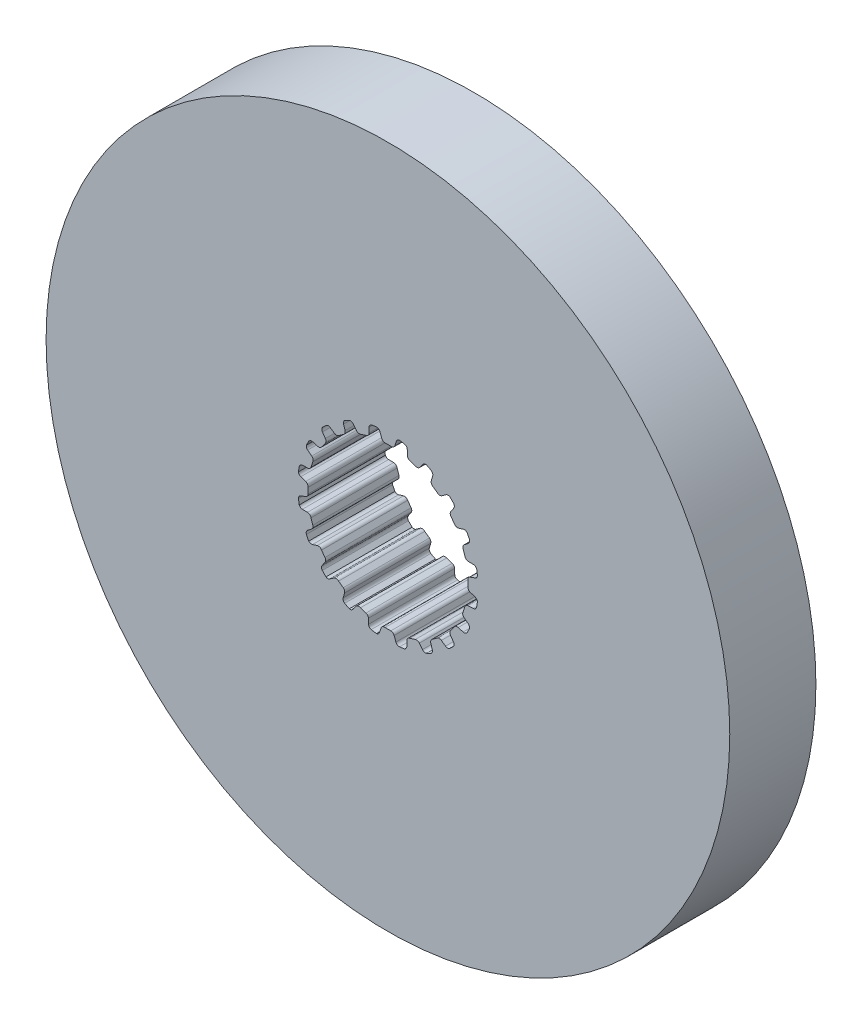
SolidWorks part; units mm, degrees
ref_plane "Front Plane" through (0, 0, 0) normal (0, 0, 1) x (1, 0, 0)
ref_plane "Top Plane" through (0, 0, 0) normal (0, 1, 0) x (1, 0, 0)
ref_plane "Right Plane" through (0, 0, 0) normal (1, 0, 0) x (0, 0, -1)
sketch "Sketch1" plane through (0, 0, 0) normal (0, 0, 1) x (1, 0, 0)
  line L0 (-0.1069, 2.9699) -> (0.1069, 2.9699)
  line L1 (0.3159, 3.2375) -> (0.2537, 3.0575)
  line L2 (-0.2964, 3.2367) -> (-0.2318, 3.0575)
  line L3 (-0.2964, 3.2367) -> (0.3159, 3.2375) construction
  line L4 (0, 3.3252) -> (0, 0) construction
  line L5 (-0.2318, 3.0575) -> (0.2537, 3.0575) construction
  line L6 (-0.4281, 3.3241) -> (0.4281, 3.3263) construction
  line L7 (0.7183, 3.1698) -> (0.7244, 2.9795)
  line L8 (0.816, 2.8576) -> (1.0195, 2.7915)
  line L9 (1.3009, 2.9815) -> (1.1862, 2.8295)
  line L10 (1.6627, 2.7927) -> (1.6097, 2.6099)
  line L11 (1.6591, 2.4655) -> (1.8322, 2.3398)
  line L12 (2.1585, 2.4335) -> (2.0025, 2.3245)
  line L13 (2.4443, 2.1423) -> (2.3374, 1.9847)
  line L14 (2.3398, 1.8322) -> (2.4655, 1.6591)
  line L15 (2.8049, 1.6474) -> (2.6228, 1.5919)
  line L16 (2.9866, 1.2821) -> (2.8363, 1.1653)
  line L17 (2.7915, 1.0195) -> (2.8576, 0.816)
  line L18 (3.1767, 0.7) -> (2.9863, 0.7035)
  line L19 (3.2367, 0.2964) -> (3.0575, 0.2318)
  line L20 (2.9699, 0.1069) -> (2.9699, -0.1069)
  line L21 (3.2375, -0.3159) -> (3.0575, -0.2537)
  line L22 (3.1698, -0.7183) -> (2.9795, -0.7244)
  line L23 (2.8576, -0.816) -> (2.7915, -1.0195)
  line L24 (2.9815, -1.3009) -> (2.8295, -1.1862)
  line L25 (2.7927, -1.6627) -> (2.6099, -1.6097)
  line L26 (2.4655, -1.6591) -> (2.3398, -1.8322)
  line L27 (2.4335, -2.1585) -> (2.3245, -2.0025)
  line L28 (2.1423, -2.4443) -> (1.9847, -2.3374)
  line L29 (1.8322, -2.3398) -> (1.6591, -2.4655)
  line L30 (1.6474, -2.8049) -> (1.5919, -2.6228)
  line L31 (1.2821, -2.9866) -> (1.1653, -2.8363)
  line L32 (1.0195, -2.7915) -> (0.816, -2.8576)
  line L33 (0.7, -3.1767) -> (0.7035, -2.9863)
  line L34 (0.2964, -3.2367) -> (0.2318, -3.0575)
  line L35 (0.1069, -2.9699) -> (-0.1069, -2.9699)
  line L36 (-0.3159, -3.2375) -> (-0.2537, -3.0575)
  line L37 (-0.7183, -3.1698) -> (-0.7244, -2.9795)
  line L38 (-0.816, -2.8576) -> (-1.0195, -2.7915)
  line L39 (-1.3009, -2.9815) -> (-1.1862, -2.8295)
  line L40 (-1.6627, -2.7927) -> (-1.6097, -2.6099)
  line L41 (-1.6591, -2.4655) -> (-1.8322, -2.3398)
  line L42 (-2.1585, -2.4335) -> (-2.0025, -2.3245)
  line L43 (-2.4443, -2.1423) -> (-2.3374, -1.9847)
  line L44 (-2.3398, -1.8322) -> (-2.4655, -1.6591)
  line L45 (-2.8049, -1.6474) -> (-2.6228, -1.5919)
  line L46 (-2.9866, -1.2821) -> (-2.8363, -1.1653)
  line L47 (-2.7915, -1.0195) -> (-2.8576, -0.816)
  line L48 (-3.1767, -0.7) -> (-2.9863, -0.7035)
  line L49 (-3.2367, -0.2964) -> (-3.0575, -0.2318)
  line L50 (-2.9699, -0.1069) -> (-2.9699, 0.1069)
  line L51 (-3.2375, 0.3159) -> (-3.0575, 0.2537)
  line L52 (-3.1698, 0.7183) -> (-2.9795, 0.7244)
  line L53 (-2.8576, 0.816) -> (-2.7915, 1.0195)
  line L54 (-2.9815, 1.3009) -> (-2.8295, 1.1862)
  line L55 (-2.7927, 1.6627) -> (-2.6099, 1.6097)
  line L56 (-2.4655, 1.6591) -> (-2.3398, 1.8322)
  line L57 (-2.4335, 2.1585) -> (-2.3245, 2.0025)
  line L58 (-2.1423, 2.4443) -> (-1.9847, 2.3374)
  line L59 (-1.8322, 2.3398) -> (-1.6591, 2.4655)
  line L60 (-1.6474, 2.8049) -> (-1.5919, 2.6228)
  line L61 (-1.2821, 2.9866) -> (-1.1653, 2.8363)
  line L62 (-1.0195, 2.7915) -> (-0.816, 2.8576)
  line L63 (-0.7, 3.1767) -> (-0.7035, 2.9863)
  line L64 (0.4281, 3.3263) -> (0.62, 3.2938)
  line L65 (1.4351, 3.0312) -> (1.6075, 2.9409)
  line L66 (2.3015, 2.4394) -> (2.4376, 2.3003)
  line L67 (2.9427, 1.6088) -> (3.0291, 1.4344)
  line L68 (3.2958, 0.6207) -> (3.3241, 0.4281)
  line L69 (3.3263, -0.4281) -> (3.2938, -0.62)
  line L70 (3.0312, -1.4351) -> (2.9409, -1.6075)
  line L71 (2.4394, -2.3015) -> (2.3003, -2.4376)
  line L72 (1.6088, -2.9427) -> (1.4344, -3.0291)
  line L73 (0.6207, -3.2958) -> (0.4281, -3.3241)
  line L74 (-0.4281, -3.3263) -> (-0.62, -3.2938)
  line L75 (-1.4351, -3.0312) -> (-1.6075, -2.9409)
  line L76 (-2.3015, -2.4394) -> (-2.4376, -2.3003)
  line L77 (-2.9427, -1.6088) -> (-3.0291, -1.4344)
  line L78 (-3.2958, -0.6207) -> (-3.3241, -0.4281)
  line L79 (-3.3263, 0.4281) -> (-3.2938, 0.62)
  line L80 (-3.0312, 1.4351) -> (-2.9409, 1.6075)
  line L81 (-2.4394, 2.3015) -> (-2.3003, 2.4376)
  line L82 (-1.6088, 2.9427) -> (-1.4344, 3.0291)
  line L83 (-0.6207, 3.2958) -> (-0.4281, 3.3241)
  arc A0 (0.2537, 3.0575) -> (0.1069, 2.9699) centre (0.1283, 3.1009) cw
  arc A1 (-0.2318, 3.0575) -> (-0.1069, 2.9699) centre (-0.1069, 3.1026) ccw
  arc A2 (0.62, 3.2938) -> (0.7183, 3.1698) centre (0.5856, 3.1656) cw
  arc A3 (0.7244, 2.9795) -> (0.816, 2.8576) centre (0.857, 2.9838) ccw
  arc A4 (-0.4281, 3.3241) -> (-0.2964, 3.2367) centre (-0.4213, 3.1916) cw
  arc A5 (0.4281, 3.3263) -> (0.3159, 3.2375) centre (0.4413, 3.1942) ccw
  arc A6 (1.1862, 2.8295) -> (1.0195, 2.7915) centre (1.0802, 2.9095) cw
  arc A7 (1.4351, 3.0312) -> (1.3009, 2.9815) centre (1.4068, 2.9015) ccw
  arc A8 (1.6075, 2.9409) -> (1.6627, 2.7927) centre (1.5352, 2.8297) cw
  arc A9 (1.6097, 2.6099) -> (1.6591, 2.4655) centre (1.7371, 2.5729) ccw
  arc A10 (2.0025, 2.3245) -> (1.8322, 2.3398) centre (1.9264, 2.4332) cw
  arc A11 (2.3015, 2.4394) -> (2.1585, 2.4335) centre (2.2346, 2.3248) ccw
  arc A12 (2.4376, 2.3003) -> (2.4443, 2.1423) centre (2.3345, 2.2168) cw
  arc A13 (2.3374, 1.9847) -> (2.3398, 1.8322) centre (2.4472, 1.9102) ccw
  arc A14 (2.6228, 1.5919) -> (2.4655, 1.6591) centre (2.5841, 1.7189) cw
  arc A15 (2.9427, 1.6088) -> (2.8049, 1.6474) centre (2.8436, 1.5205) ccw
  arc A16 (3.0291, 1.4344) -> (2.9866, 1.2821) centre (2.9052, 1.3869) cw
  arc A17 (2.8363, 1.1653) -> (2.7915, 1.0195) centre (2.9177, 1.0605) ccw
  arc A18 (2.9863, 0.7035) -> (2.8576, 0.816) centre (2.9887, 0.8362) cw
  arc A19 (3.2958, 0.6207) -> (3.1767, 0.7) centre (3.1743, 0.5673) ccw
  arc A20 (3.3241, 0.4281) -> (3.2367, 0.2964) centre (3.1916, 0.4213) cw
  arc A21 (3.0575, 0.2318) -> (2.9699, 0.1069) centre (3.1026, 0.1069) ccw
  arc A22 (3.0575, -0.2537) -> (2.9699, -0.1069) centre (3.1009, -0.1283) cw
  arc A23 (3.3263, -0.4281) -> (3.2375, -0.3159) centre (3.1942, -0.4413) ccw
  arc A24 (3.2938, -0.62) -> (3.1698, -0.7183) centre (3.1656, -0.5856) cw
  arc A25 (2.9795, -0.7244) -> (2.8576, -0.816) centre (2.9838, -0.857) ccw
  arc A26 (2.8295, -1.1862) -> (2.7915, -1.0195) centre (2.9095, -1.0802) cw
  arc A27 (3.0312, -1.4351) -> (2.9815, -1.3009) centre (2.9015, -1.4068) ccw
  arc A28 (2.9409, -1.6075) -> (2.7927, -1.6627) centre (2.8297, -1.5352) cw
  arc A29 (2.6099, -1.6097) -> (2.4655, -1.6591) centre (2.5729, -1.7371) ccw
  arc A30 (2.3245, -2.0025) -> (2.3398, -1.8322) centre (2.4332, -1.9264) cw
  arc A31 (2.4394, -2.3015) -> (2.4335, -2.1585) centre (2.3248, -2.2346) ccw
  arc A32 (2.3003, -2.4376) -> (2.1423, -2.4443) centre (2.2168, -2.3345) cw
  arc A33 (1.9847, -2.3374) -> (1.8322, -2.3398) centre (1.9102, -2.4472) ccw
  arc A34 (1.5919, -2.6228) -> (1.6591, -2.4655) centre (1.7189, -2.5841) cw
  arc A35 (1.6088, -2.9427) -> (1.6474, -2.8049) centre (1.5205, -2.8436) ccw
  arc A36 (1.4344, -3.0291) -> (1.2821, -2.9866) centre (1.3869, -2.9052) cw
  arc A37 (1.1653, -2.8363) -> (1.0195, -2.7915) centre (1.0605, -2.9177) ccw
  arc A38 (0.7035, -2.9863) -> (0.816, -2.8576) centre (0.8362, -2.9887) cw
  arc A39 (0.6207, -3.2958) -> (0.7, -3.1767) centre (0.5673, -3.1743) ccw
  arc A40 (0.4281, -3.3241) -> (0.2964, -3.2367) centre (0.4213, -3.1916) cw
  arc A41 (0.2318, -3.0575) -> (0.1069, -2.9699) centre (0.1069, -3.1026) ccw
  arc A42 (-0.2537, -3.0575) -> (-0.1069, -2.9699) centre (-0.1283, -3.1009) cw
  arc A43 (-0.4281, -3.3263) -> (-0.3159, -3.2375) centre (-0.4413, -3.1942) ccw
  arc A44 (-0.62, -3.2938) -> (-0.7183, -3.1698) centre (-0.5856, -3.1656) cw
  arc A45 (-0.7244, -2.9795) -> (-0.816, -2.8576) centre (-0.857, -2.9838) ccw
  arc A46 (-1.1862, -2.8295) -> (-1.0195, -2.7915) centre (-1.0802, -2.9095) cw
  arc A47 (-1.4351, -3.0312) -> (-1.3009, -2.9815) centre (-1.4068, -2.9015) ccw
  arc A48 (-1.6075, -2.9409) -> (-1.6627, -2.7927) centre (-1.5352, -2.8297) cw
  arc A49 (-1.6097, -2.6099) -> (-1.6591, -2.4655) centre (-1.7371, -2.5729) ccw
  arc A50 (-2.0025, -2.3245) -> (-1.8322, -2.3398) centre (-1.9264, -2.4332) cw
  arc A51 (-2.3015, -2.4394) -> (-2.1585, -2.4335) centre (-2.2346, -2.3248) ccw
  arc A52 (-2.4376, -2.3003) -> (-2.4443, -2.1423) centre (-2.3345, -2.2168) cw
  arc A53 (-2.3374, -1.9847) -> (-2.3398, -1.8322) centre (-2.4472, -1.9102) ccw
  arc A54 (-2.6228, -1.5919) -> (-2.4655, -1.6591) centre (-2.5841, -1.7189) cw
  arc A55 (-2.9427, -1.6088) -> (-2.8049, -1.6474) centre (-2.8436, -1.5205) ccw
  arc A56 (-3.0291, -1.4344) -> (-2.9866, -1.2821) centre (-2.9052, -1.3869) cw
  arc A57 (-2.8363, -1.1653) -> (-2.7915, -1.0195) centre (-2.9177, -1.0605) ccw
  arc A58 (-2.9863, -0.7035) -> (-2.8576, -0.816) centre (-2.9887, -0.8362) cw
  arc A59 (-3.2958, -0.6207) -> (-3.1767, -0.7) centre (-3.1743, -0.5673) ccw
  arc A60 (-3.3241, -0.4281) -> (-3.2367, -0.2964) centre (-3.1916, -0.4213) cw
  arc A61 (-3.0575, -0.2318) -> (-2.9699, -0.1069) centre (-3.1026, -0.1069) ccw
  arc A62 (-3.0575, 0.2537) -> (-2.9699, 0.1069) centre (-3.1009, 0.1283) cw
  arc A63 (-3.3263, 0.4281) -> (-3.2375, 0.3159) centre (-3.1942, 0.4413) ccw
  arc A64 (-3.2938, 0.62) -> (-3.1698, 0.7183) centre (-3.1656, 0.5856) cw
  arc A65 (-2.9795, 0.7244) -> (-2.8576, 0.816) centre (-2.9838, 0.857) ccw
  arc A66 (-2.8295, 1.1862) -> (-2.7915, 1.0195) centre (-2.9095, 1.0802) cw
  arc A67 (-3.0312, 1.4351) -> (-2.9815, 1.3009) centre (-2.9015, 1.4068) ccw
  arc A68 (-2.9409, 1.6075) -> (-2.7927, 1.6627) centre (-2.8297, 1.5352) cw
  arc A69 (-2.6099, 1.6097) -> (-2.4655, 1.6591) centre (-2.5729, 1.7371) ccw
  arc A70 (-2.3245, 2.0025) -> (-2.3398, 1.8322) centre (-2.4332, 1.9264) cw
  arc A71 (-2.4394, 2.3015) -> (-2.4335, 2.1585) centre (-2.3248, 2.2346) ccw
  arc A72 (-2.3003, 2.4376) -> (-2.1423, 2.4443) centre (-2.2168, 2.3345) cw
  arc A73 (-1.9847, 2.3374) -> (-1.8322, 2.3398) centre (-1.9102, 2.4472) ccw
  arc A74 (-1.5919, 2.6228) -> (-1.6591, 2.4655) centre (-1.7189, 2.5841) cw
  arc A75 (-1.6088, 2.9427) -> (-1.6474, 2.8049) centre (-1.5205, 2.8436) ccw
  arc A76 (-1.4344, 3.0291) -> (-1.2821, 2.9866) centre (-1.3869, 2.9052) cw
  arc A77 (-1.1653, 2.8363) -> (-1.0195, 2.7915) centre (-1.0605, 2.9177) ccw
  arc A78 (-0.7035, 2.9863) -> (-0.816, 2.8576) centre (-0.8362, 2.9887) cw
  arc A79 (-0.6207, 3.2958) -> (-0.7, 3.1767) centre (-0.5673, 3.1743) ccw
  circle A80 centre (0, 0) radius 12.7
  point P14 (0, 2.9699)
  point P247 (0, 0)
  dimension "D4" = 0.1327
  dimension "D8" = 20
  dimension "D9" = 25.4
  dimension "D1" = 2.9699
  dimension "D2" = 0.2139
  dimension "D3" = 0.1904
  dimension "D5" = 0.0877
  dimension "D6" = 0.4855
  dimension "D7" = 0.8563
extrude "Boss-Extrude1" add sketch "Sketch1" along normal blind 3.2004
